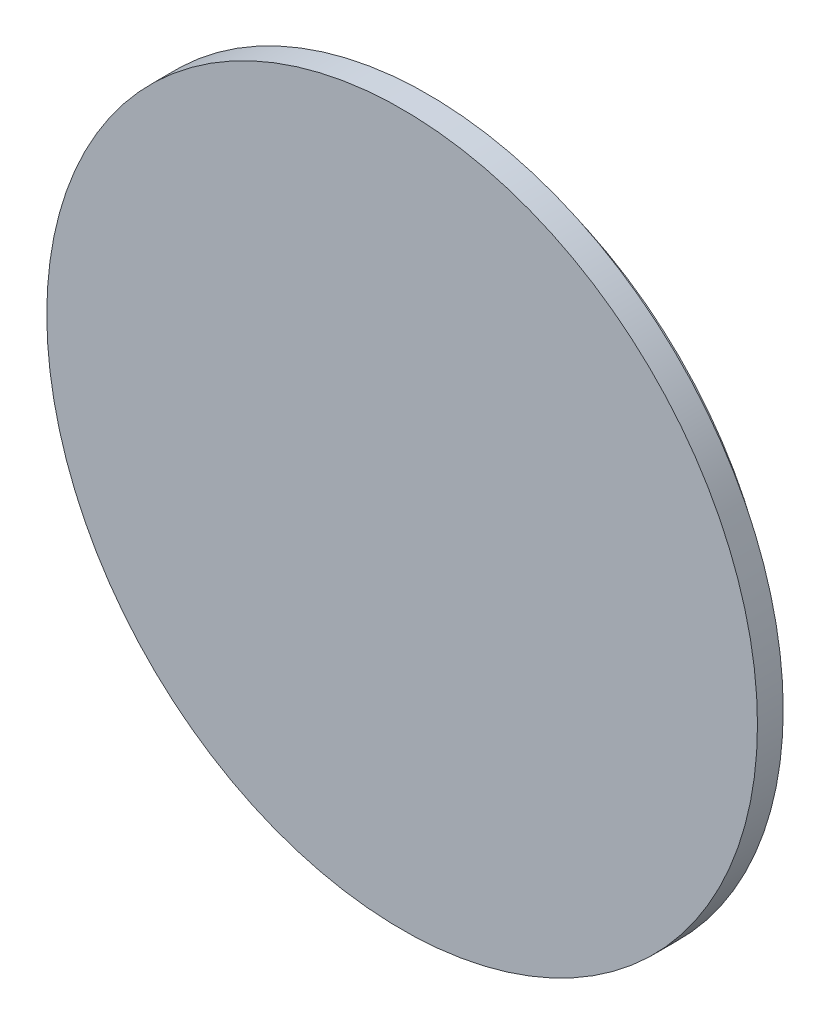
SolidWorks part; units mm, degrees
material "PET"
ref_plane "Front Plane" through (0, 0, 0) normal (0, 0, 1) x (1, 0, 0)
ref_plane "Top Plane" through (0, 0, 0) normal (0, 1, 0) x (1, 0, 0)
ref_plane "Right Plane" through (0, 0, 0) normal (1, 0, 0) x (0, 0, -1)
sketch "Sketch1" plane through (0, 0, 0) normal (0, 0, 1) x (1, 0, 0)
  circle A0 centre (0, 0) radius 34.5
  dimension "D1" = 69
extrude "Boss-Extrude1" add sketch "Sketch1" along normal blind 4.5
sketch "Sketch2" plane through (0, 0, 0) normal (0, 1, 0) x (1, 0, 0)
  line L1 (34.5, 0) -> (31.85, 0)
  line L2 (34.5, 0) -> (34.5, -2)
  line L3 (34.5, -2) -> (31.85, -2)
  line L4 (31.85, 0) -> (31.85, -2)
  dimension "D1" = 2.65
  dimension "D2" = 2
sketch "Sketch3" plane through (0, 0, 0) normal (0, 1, 0) x (1, 0, 0)
  line L0 (0, 0) -> (0, -4.5) construction
revolve "Cut-Revolve1" cut sketch "Sketch2" angle 360 about L0
sketch "Sketch4" plane through (0, 0, 0) normal (0, 1, 0) x (1, 0, 0)
  line L0 (31.85, 0) -> (-31.85, 0) construction
  line L1 (-0.775, 0) -> (0.775, 0)
  line L2 (-0.775, 0) -> (-0.775, -1.5)
  line L3 (-0.775, -1.5) -> (0.775, -1.5)
  line L4 (0.775, 0) -> (0.775, -1.5)
  line L5 (0, 200000) -> (0, -200004.5) construction
  dimension "D1" = 1.5
  dimension "D2" = 1.55
  dimension "D3" = 0.775
extrude "Cut-Extrude1" cut sketch "Sketch4" against normal through all both and the other way through all
